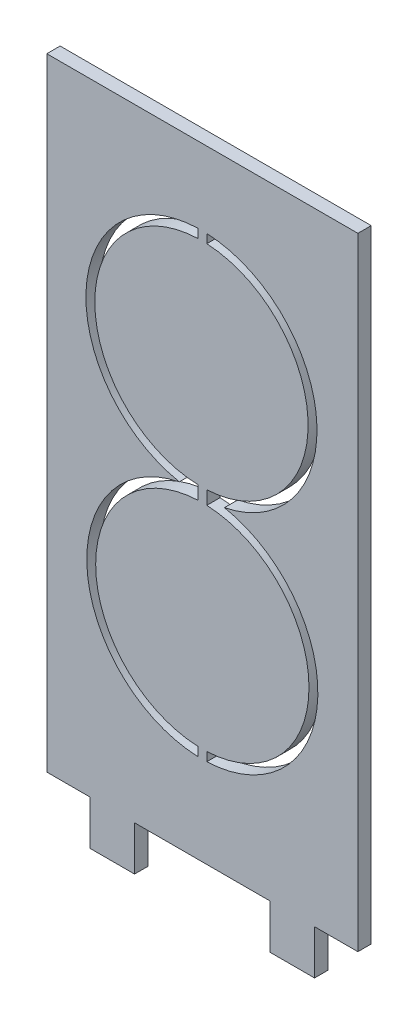
SolidWorks part; units mm, degrees
material "Glas"
ref_plane "Ebene vorne" through (0, 0, 0) normal (0, 0, 1) x (1, 0, 0)
ref_plane "Ebene oben" through (0, 0, 0) normal (0, 1, 0) x (1, 0, 0)
ref_plane "Ebene rechts" through (0, 0, 0) normal (1, 0, 0) x (0, 0, -1)
sketch "Skizze1" plane through (0, 0, 0) normal (0, 0, 1) x (1, 0, 0)
  line L1 (0, 0) -> (35, 0)
  line L2 (0, 0) -> (0, 75)
  line L3 (0, 75) -> (35, 75)
  line L4 (35, 0) -> (35, 75)
  dimension "D1" = 35
  dimension "D2" = 75
extrude "Aufsatz-Linear austragen1" add sketch "Skizze1" along normal blind 1.5
sketch "Skizze3" plane through (0, 0, 1.5) normal (0, 0, 1) x (1, 0, 0)
  line L0 (0, 0) -> (35, 0) construction
  line L1 (9.875, 0) -> (25.125, 0)
  line L2 (9.875, 0) -> (9.875, 5)
  line L3 (9.875, 5) -> (25.125, 5)
  line L4 (25.125, 0) -> (25.125, 5)
  line L5 (35, 0) -> (35, 75) construction
  line L6 (30.125, 5) -> (35, 5)
  line L7 (30.125, 5) -> (30.125, 0)
  line L8 (30.125, 0) -> (35, 0)
  line L9 (35, 5) -> (35, 0)
  line L10 (4.875, 5) -> (0, 5)
  line L11 (4.875, 5) -> (4.875, 0)
  line L12 (4.875, 0) -> (0, 0)
  line L13 (0, 5) -> (0, 0)
  dimension "D1" = 4.875
  dimension "D2" = 4.875
  dimension "D3" = 0
  dimension "D4" = 5
  dimension "D5" = 5
  dimension "D6" = 5
  dimension "D7" = 5
extrude "Schnitt-Linear austragen12" cut sketch "Skizze3" against normal blind 20
sketch "Skizze13" plane through (0, 0, 1.5) normal (0, 0, 1) x (1, 0, 0)
  line L0 (35, 75) -> (0, 75) construction
  line L1 (25.125, 5) -> (9.875, 5) construction
  line L2 (35, 5) -> (35, 75) construction
  line L3 (14.9058, 40.7415) -> (14.9133, 40.7401)
  circle A0 centre (17.4, 53.5) radius 12
  circle A1 centre (17.5, 28) radius 12
  arc A6 (19.9867, 40.7599) -> (14.9133, 40.7401) centre (17.5, 28) cw
  arc A7 (19.9867, 40.7599) -> (14.9058, 40.7415) centre (17.4, 53.5) ccw
  dimension "D2" = 13
  dimension "D3" = 24
  dimension "D4" = 24
  dimension "D6" = 21.5
  dimension "D7" = 23
  dimension "D8" = 17.6
  dimension "D9" = 17.5
extrude "Schnitt-Linear austragen18" cut sketch "Skizze13" against normal blind 1.5
sketch "Skizze14" plane through (0, 0, 1.5) normal (0, 0, 1) x (1, 0, 0)
  line L0 (35, 5) -> (35, 75) construction
  line L1 (17, 68.1857) -> (18, 68.1857)
  line L2 (17, 68.1857) -> (17, 10.8736)
  line L3 (17, 10.8736) -> (18, 10.8736)
  line L4 (18, 68.1857) -> (18, 10.8736)
  dimension "D1" = 1
  dimension "D2" = 17
extrude "Aufsatz-Linear austragen8" add sketch "Skizze14" against normal blind 1.5
